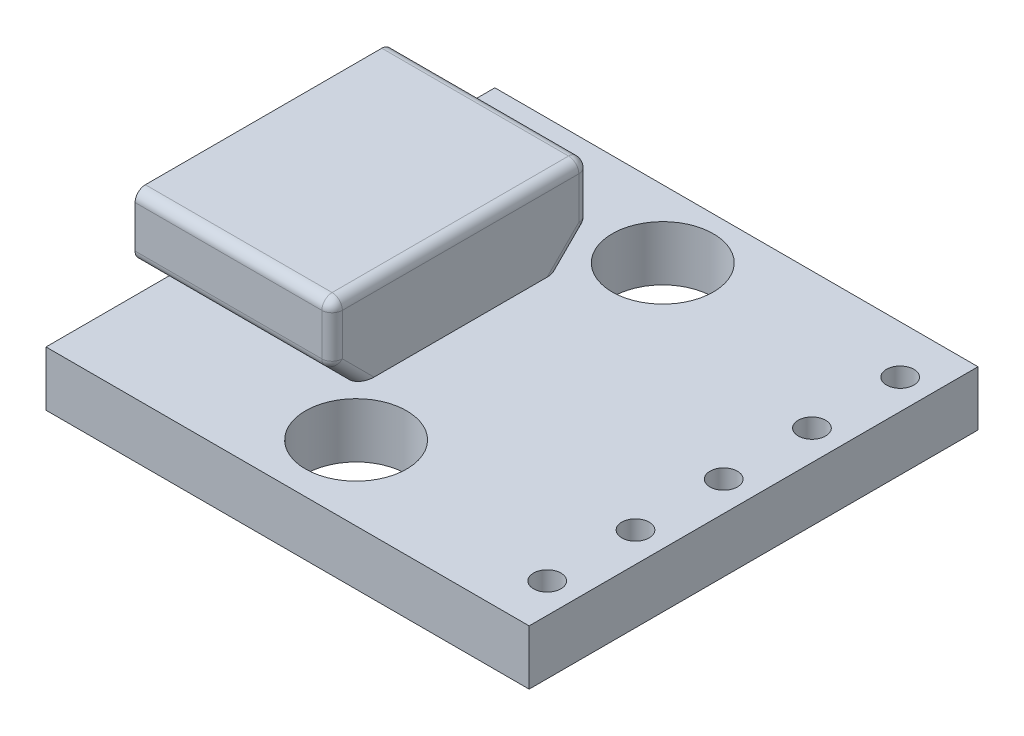
SolidWorks part; units mm, degrees
ref_plane "Plan de face" through (0, 0, 0) normal (0, 0, 1) x (1, 0, 0)
ref_plane "Plan de dessus" through (0, 0, 0) normal (0, 1, 0) x (1, 0, 0)
ref_plane "Plan de droite" through (0, 0, 0) normal (1, 0, 0) x (0, 0, -1)
sketch "Esquisse1" plane through (0, 0, 0) normal (0, 1, 0) x (1, 0, 0)
  line L1 (-7.05, -6.55) -> (7.05, -6.55)
  line L2 (-7.05, -6.55) -> (-7.05, 6.55)
  line L3 (-7.05, 6.55) -> (7.05, 6.55)
  line L4 (7.05, -6.55) -> (7.05, 6.55)
  line L5 (-7.05, -6.55) -> (7.05, 6.55) construction
  line L6 (-7.05, 6.55) -> (7.05, -6.55) construction
  circle A0 centre (-0.175, -4.375) radius 1.475
  circle A1 centre (-0.175, 4.575) radius 1.475
  circle A2 centre (6.1788, -5.15) radius 0.4
  circle A3 centre (6.1788, -2.575) radius 0.4
  circle A4 centre (6.1788, 0) radius 0.4
  circle A5 centre (6.1788, 2.575) radius 0.4
  circle A6 centre (6.1788, 5.15) radius 0.4
  point P0 (0, 0)
  point P10 (-0.175, -5.85)
  point P11 (-1.65, 4.575)
  point P12 (-0.175, 6.05)
  point P13 (-1.65, -4.375)
  point P24 (6.1788, 5.55)
  point P25 (6.1788, -5.55)
  dimension "D3" = 2.95
  dimension "D4" = 2.95
  dimension "D8" = 0.8
  dimension "D9" = 0.8
  dimension "D10" = 0.8
  dimension "D11" = 0.8
  dimension "D12" = 0.8
  dimension "D1" = 14.1
  dimension "D2" = 13.1
  dimension "D5" = 0.5
  dimension "D6" = 0.7
  dimension "D7" = 5.4
  dimension "D13" = 1
  dimension "D14" = 1
  dimension "D15" = 2.575
  dimension "D16" = 2.575
  dimension "D17" = 2.575
extrude "Boss.-Extru.1" add sketch "Esquisse1" along normal blind 1.6
sketch "Esquisse2" plane through (0, 1.6, 0) normal (0, 1, 0) x (1, 0, 0)
  line L0 (-7.05, 6.55) -> (-7.05, -6.55) construction
  line L1 (-7.25, -3.75) -> (-1.5, -3.75)
  line L2 (-7.25, -3.75) -> (-7.25, 3.75)
  line L3 (-7.25, 3.75) -> (-1.5, 3.75)
  line L4 (-1.5, -3.75) -> (-1.5, 3.75)
  point P6 (-1.5, 0)
  dimension "D1" = 0.2
  dimension "D2" = 5.75
  dimension "D3" = 7.5
extrude "Boss.-Extru.2" add sketch "Esquisse2" along normal blind 2.45
sketch "Esquisse3" plane through (-7.25, 0, 0) normal (-1, 0, 0) x (0, 0, 1)
  line L0 (-3.75, 1.6) -> (-2.95, 1.6)
  line L1 (-3.75, 1.6) -> (3.75, 1.6) construction
  line L2 (-2.95, 1.6) -> (-3.75, 2.4)
  line L3 (-3.75, 4.05) -> (-3.75, 1.6) construction
  line L4 (-3.75, 2.4) -> (-3.75, 1.6)
  line L5 (2.95, 1.6) -> (3.75, 1.6)
  line L6 (-3.75, 1.6) -> (3.75, 1.6) construction
  line L7 (3.75, 1.6) -> (3.75, 2.4)
  line L8 (3.75, 4.05) -> (3.75, 1.6) construction
  line L9 (3.75, 2.4) -> (2.95, 1.6)
  dimension "D1" = 0.8
  dimension "D2" = 0.8
  dimension "D3" = 0.8
  dimension "D4" = 0.8
extrude "Enlèv. mat.-Extru.1" cut sketch "Esquisse3" against normal up to surface (5.75 mm away) up to face at (-1.5, 2.58, 0.7454)
fillet "Congé1" radius 0.3 11 edges at (-1.5, 2, 3.35) (-1.5, 3.225, 3.75) (-1.5, 2, -3.35) (-1.5, 3.225, -3.75) (-1.5, 4.05, 0) (-7.15, 1.6, 2.95) (-7.15, 1.6, -2.95) (-4.375, 2.4, -3.75) (-4.375, 2.4, 3.75) (-4.375, 4.05, -3.75) (-4.375, 4.05, 3.75)
sketch "Esquisse4" plane through (-7.25, 0, 0) normal (-1, 0, 0) x (0, 0, 1)
  line L0 (-3.53, 3.83) -> (-3.53, 2.4911)
  line L1 (-3.53, 2.4911) -> (-2.8589, 1.82)
  line L2 (-2.8589, 1.82) -> (2.8589, 1.82)
  line L3 (2.8589, 1.82) -> (3.53, 2.4911)
  line L4 (3.53, 2.4911) -> (3.53, 3.83)
  line L5 (3.53, 3.83) -> (-3.53, 3.83)
  line L6 (-3.45, 4.05) -> (3.45, 4.05) construction
  line L7 (-3.75, 3.75) -> (-3.75, 2.5243) construction
  line L8 (3.75, 3.75) -> (3.75, 2.5243) construction
  line L10 (-3.0379, 1.6879) -> (-3.6621, 2.3121) construction
  line L11 (3.6621, 2.3121) -> (3.0379, 1.6879) construction
  line L12 (-2.8257, 1.6) -> (2.8257, 1.6) construction
  dimension "D1" = 0.22
  dimension "D2" = 0.22
  dimension "D3" = 0.22
  dimension "D4" = 0.22
  dimension "D5" = 0.22
  dimension "D6" = 0.22
extrude "Enlèv. mat.-Extru.2" cut sketch "Esquisse4" against normal blind 4.5
sketch "Esquisse5" plane through (-2.75, 0, 0) normal (-1, 0, 0) x (0, 0, 1)
  line L1 (-1.75, 2.53) -> (1.75, 2.53)
  line L2 (-1.75, 2.53) -> (-1.75, 3.13)
  line L3 (-1.75, 3.13) -> (1.75, 3.13)
  line L4 (1.75, 2.53) -> (1.75, 3.13)
  line L5 (3.53, 3.83) -> (-3.53, 3.83) construction
  line L6 (-2.8589, 1.82) -> (2.8589, 1.82) construction
  point P6 (-1.75, 2.83)
  point P9 (0, 2.53)
  point P10 (0, 1.82)
  dimension "D1" = 3.5
  dimension "D2" = 0.6
  dimension "D3" = 1
extrude "Boss.-Extru.3" add sketch "Esquisse5" along normal blind 3.7
